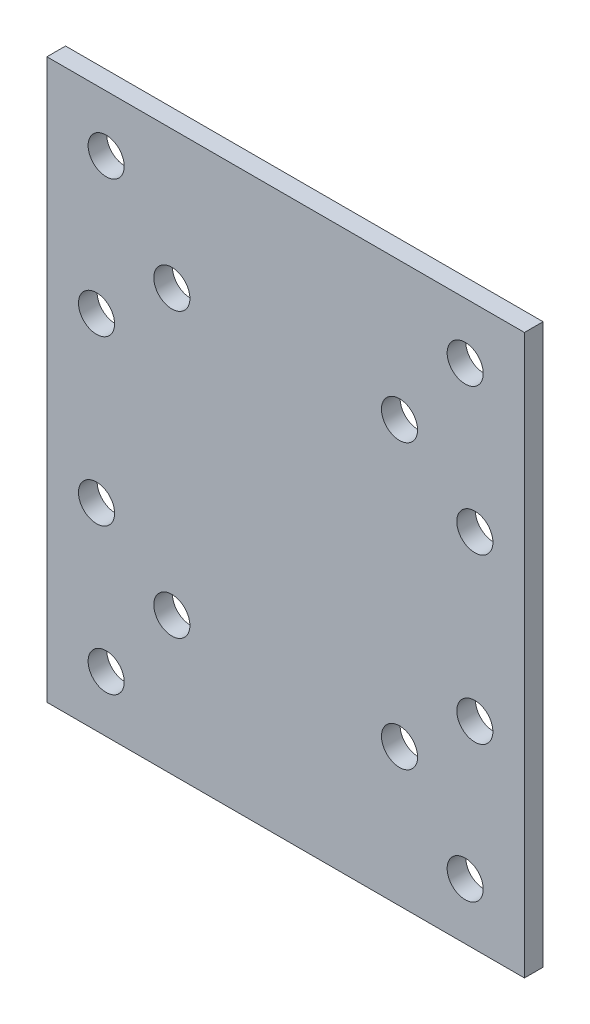
SolidWorks part; units mm, degrees
ref_plane "Front Plane" through (0, 0, 0) normal (0, 0, 1) x (1, 0, 0)
ref_plane "Top Plane" through (0, 0, 0) normal (0, 1, 0) x (1, 0, 0)
ref_plane "Right Plane" through (0, 0, 0) normal (1, 0, 0) x (0, 0, -1)
sketch "Sketch1" plane through (0, 0, 0) normal (0, 0, 1) x (1, 0, 0)
  line L0 (205, 480) -> (205, 0) construction
  line L1 (0, 0) -> (410, 0)
  line L2 (0, 0) -> (0, 480)
  line L3 (0, 480) -> (410, 480)
  line L4 (410, 0) -> (410, 480)
  line L5 (0, 240) -> (205, 240) construction
  line L6 (205, 240) -> (410, 240) construction
  line L7 (205, 240) -> (2120, 240) construction
  line L8 (2120, 240) -> (2120, 1070) construction
  line L9 (2120, 1070) -> (205, 240) construction
  line L10 (205, 240) -> (205, -2248) construction
  line L11 (205, -2248) -> (-1795, -2248) construction
  line L12 (-1795, -2248) -> (205, 240) construction
  circle A0 centre (367.4022, 310.3884) radius 15.5
  circle A1 centre (107.2618, 118.4137) radius 15.5
  circle A2 centre (50.8743, 48.2677) radius 15.5
  circle A3 centre (42.5978, 310.3884) radius 15.5
  circle A4 centre (359.1257, 48.2677) radius 15.5
  circle A5 centre (302.7382, 118.4137) radius 15.5
  circle A6 centre (367.4022, 169.6116) radius 15.5
  circle A7 centre (50.8743, 431.7323) radius 15.5
  circle A8 centre (107.2618, 361.5863) radius 15.5
  circle A9 centre (42.5978, 169.6116) radius 15.5
  circle A10 centre (302.7382, 361.5863) radius 15.5
  circle A11 centre (359.1257, 431.7323) radius 15.5
  dimension "D7" = 31
  dimension "D9" = 31
  dimension "D11" = 31
  dimension "D1" = 410
  dimension "D2" = 480
  dimension "D3" = 1915
  dimension "D4" = 830
  dimension "D5" = 2000
  dimension "D6" = 2488
  dimension "D8" = 177
  dimension "D10" = 156
  dimension "D12" = 90
extrude "Extrude1" add sketch "Sketch1" along normal blind 16
